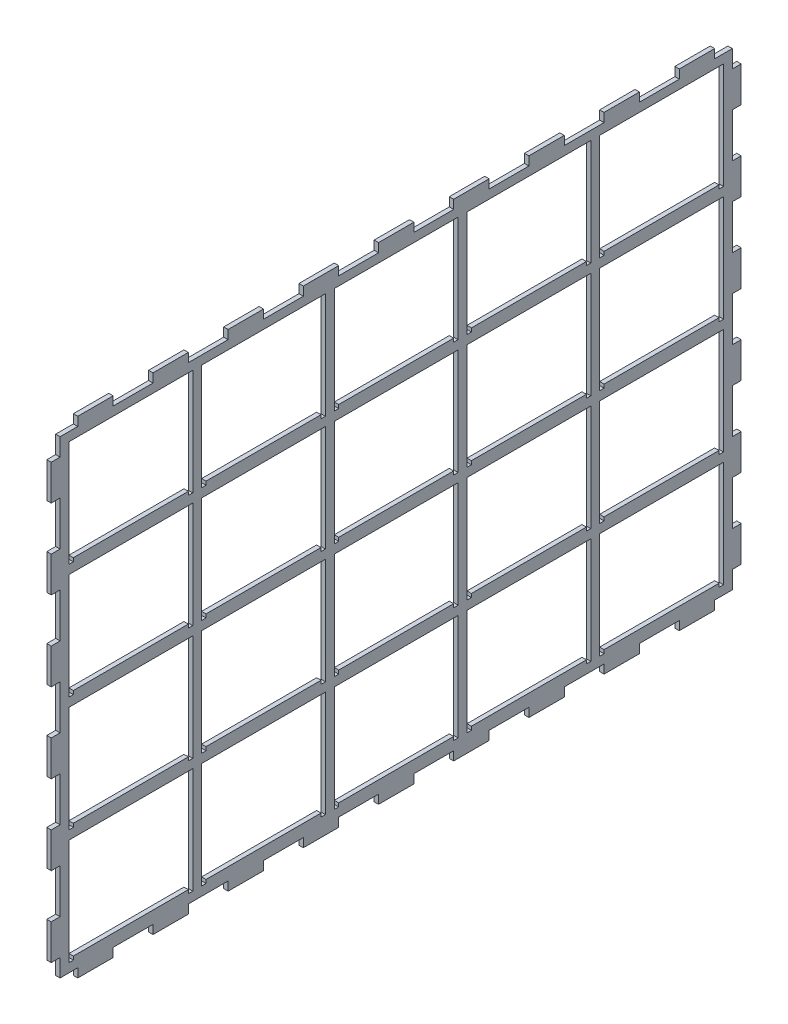
SolidWorks part; units mm, degrees
material "Mahogany"
ref_plane "Front" through (0, 0, 0) normal (0, 0, 1) x (1, 0, 0)
ref_plane "Top" through (0, 0, 0) normal (0, 1, 0) x (1, 0, 0)
ref_plane "Right" through (0, 0, 0) normal (1, 0, 0) x (0, 0, -1)
sketch "Sketch1" plane through (0, 0, 0) normal (1, 0, 0) x (0, 0, -1)
  line L0 (115, 67.5) -> (115, 127.5)
  line L1 (115, 127.5) -> (185, 127.5)
  line L2 (185, 127.5) -> (185, 67.5)
  line L3 (185, 67.5) -> (182.5, 67.5)
  line L4 (182.5, 67.5) -> (182.5, 69.5)
  line L5 (117.5, 69.5) -> (182.5, 69.5)
  line L6 (117.5, 67.5) -> (117.5, 69.5)
  line L7 (117.5, 67.5) -> (115, 67.5)
  line L8 (-190, -132.5) -> (-190, 132.5) construction
  line L9 (-195, -137.5) -> (195, -137.5) construction
  line L10 (-195, -137.5) -> (-195, 137.5) construction
  line L11 (-195, 137.5) -> (195, 137.5) construction
  line L12 (195, -137.5) -> (195, 137.5) construction
  line L13 (-195, -137.5) -> (195, 137.5) construction
  line L14 (-195, 137.5) -> (195, -137.5) construction
  line L15 (-190, 132.5) -> (190, 132.5) construction
  line L16 (190, -132.5) -> (190, 132.5) construction
  line L17 (-190, -132.5) -> (190, -132.5) construction
  line L19 (-180, 137.5) -> (-160, 137.5) construction
  line L20 (-180, 137.5) -> (-180, 132.5)
  line L21 (-180, 132.5) -> (-160, 132.5) construction
  line L22 (-160, 137.5) -> (-160, 132.5)
  line L23 (-180, 137.5) -> (-160, 132.5) construction
  line L24 (-180, 132.5) -> (-160, 137.5) construction
  line L25 (-22.8777, 0) -> (32.9465, 0) construction
  line L27 (0, 22.6378) -> (0, -11.8795) construction
  line L29 (115, 2.5) -> (115, 62.5)
  line L30 (115, 62.5) -> (185, 62.5)
  line L31 (185, 62.5) -> (185, 2.5)
  line L32 (185, 2.5) -> (182.5, 2.5)
  line L33 (182.5, 2.5) -> (182.5, 4.5)
  line L34 (117.5, 4.5) -> (182.5, 4.5)
  line L35 (117.5, 2.5) -> (117.5, 4.5)
  line L36 (117.5, 2.5) -> (115, 2.5)
  line L37 (115, -62.5) -> (115, -2.5)
  line L38 (115, -2.5) -> (185, -2.5)
  line L39 (185, -2.5) -> (185, -62.5)
  line L40 (185, -62.5) -> (182.5, -62.5)
  line L41 (182.5, -62.5) -> (182.5, -60.5)
  line L42 (117.5, -60.5) -> (182.5, -60.5)
  line L43 (117.5, -62.5) -> (117.5, -60.5)
  line L44 (117.5, -62.5) -> (115, -62.5)
  line L45 (115, -127.5) -> (115, -67.5)
  line L46 (115, -67.5) -> (185, -67.5)
  line L47 (185, -67.5) -> (185, -127.5)
  line L48 (185, -127.5) -> (182.5, -127.5)
  line L49 (182.5, -127.5) -> (182.5, -125.5)
  line L50 (117.5, -125.5) -> (182.5, -125.5)
  line L51 (117.5, -127.5) -> (117.5, -125.5)
  line L52 (117.5, -127.5) -> (115, -127.5)
  line L53 (40, 67.5) -> (40, 127.5)
  line L54 (40, 127.5) -> (110, 127.5)
  line L55 (110, 127.5) -> (110, 67.5)
  line L56 (110, 67.5) -> (107.5, 67.5)
  line L57 (107.5, 67.5) -> (107.5, 69.5)
  line L58 (42.5, 69.5) -> (107.5, 69.5)
  line L59 (42.5, 67.5) -> (42.5, 69.5)
  line L60 (42.5, 67.5) -> (40, 67.5)
  line L61 (40, 2.5) -> (40, 62.5)
  line L62 (40, 62.5) -> (110, 62.5)
  line L63 (110, 62.5) -> (110, 2.5)
  line L64 (110, 2.5) -> (107.5, 2.5)
  line L65 (107.5, 2.5) -> (107.5, 4.5)
  line L66 (42.5, 4.5) -> (107.5, 4.5)
  line L67 (42.5, 2.5) -> (42.5, 4.5)
  line L68 (42.5, 2.5) -> (40, 2.5)
  line L69 (40, -62.5) -> (40, -2.5)
  line L70 (40, -2.5) -> (110, -2.5)
  line L71 (110, -2.5) -> (110, -62.5)
  line L72 (110, -62.5) -> (107.5, -62.5)
  line L73 (107.5, -62.5) -> (107.5, -60.5)
  line L74 (42.5, -60.5) -> (107.5, -60.5)
  line L75 (42.5, -62.5) -> (42.5, -60.5)
  line L76 (42.5, -62.5) -> (40, -62.5)
  line L77 (40, -127.5) -> (40, -67.5)
  line L78 (40, -67.5) -> (110, -67.5)
  line L79 (110, -67.5) -> (110, -127.5)
  line L80 (110, -127.5) -> (107.5, -127.5)
  line L81 (107.5, -127.5) -> (107.5, -125.5)
  line L82 (42.5, -125.5) -> (107.5, -125.5)
  line L83 (42.5, -127.5) -> (42.5, -125.5)
  line L84 (42.5, -127.5) -> (40, -127.5)
  line L85 (-35, 67.5) -> (-35, 127.5)
  line L86 (-35, 127.5) -> (35, 127.5)
  line L87 (35, 127.5) -> (35, 67.5)
  line L88 (35, 67.5) -> (32.5, 67.5)
  line L89 (32.5, 67.5) -> (32.5, 69.5)
  line L90 (-32.5, 69.5) -> (32.5, 69.5)
  line L91 (-32.5, 67.5) -> (-32.5, 69.5)
  line L92 (-32.5, 67.5) -> (-35, 67.5)
  line L93 (-35, 2.5) -> (-35, 62.5)
  line L94 (-35, 62.5) -> (35, 62.5)
  line L95 (35, 62.5) -> (35, 2.5)
  line L96 (35, 2.5) -> (32.5, 2.5)
  line L97 (32.5, 2.5) -> (32.5, 4.5)
  line L98 (-32.5, 4.5) -> (32.5, 4.5)
  line L99 (-32.5, 2.5) -> (-32.5, 4.5)
  line L100 (-32.5, 2.5) -> (-35, 2.5)
  line L101 (-35, -62.5) -> (-35, -2.5)
  line L102 (-35, -2.5) -> (35, -2.5)
  line L103 (35, -2.5) -> (35, -62.5)
  line L104 (35, -62.5) -> (32.5, -62.5)
  line L105 (32.5, -62.5) -> (32.5, -60.5)
  line L106 (-32.5, -60.5) -> (32.5, -60.5)
  line L107 (-32.5, -62.5) -> (-32.5, -60.5)
  line L108 (-32.5, -62.5) -> (-35, -62.5)
  line L109 (-35, -127.5) -> (-35, -67.5)
  line L110 (-35, -67.5) -> (35, -67.5)
  line L111 (35, -67.5) -> (35, -127.5)
  line L112 (35, -127.5) -> (32.5, -127.5)
  line L113 (32.5, -127.5) -> (32.5, -125.5)
  line L114 (-32.5, -125.5) -> (32.5, -125.5)
  line L115 (-32.5, -127.5) -> (-32.5, -125.5)
  line L116 (-32.5, -127.5) -> (-35, -127.5)
  line L117 (-110, 67.5) -> (-110, 127.5)
  line L118 (-110, 127.5) -> (-40, 127.5)
  line L119 (-40, 127.5) -> (-40, 67.5)
  line L120 (-40, 67.5) -> (-42.5, 67.5)
  line L121 (-42.5, 67.5) -> (-42.5, 69.5)
  line L122 (-107.5, 69.5) -> (-42.5, 69.5)
  line L123 (-107.5, 67.5) -> (-107.5, 69.5)
  line L124 (-107.5, 67.5) -> (-110, 67.5)
  line L125 (-110, 2.5) -> (-110, 62.5)
  line L126 (-110, 62.5) -> (-40, 62.5)
  line L127 (-40, 62.5) -> (-40, 2.5)
  line L128 (-40, 2.5) -> (-42.5, 2.5)
  line L129 (-42.5, 2.5) -> (-42.5, 4.5)
  line L130 (-107.5, 4.5) -> (-42.5, 4.5)
  line L131 (-107.5, 2.5) -> (-107.5, 4.5)
  line L132 (-107.5, 2.5) -> (-110, 2.5)
  line L133 (-110, -62.5) -> (-110, -2.5)
  line L134 (-110, -2.5) -> (-40, -2.5)
  line L135 (-40, -2.5) -> (-40, -62.5)
  line L136 (-40, -62.5) -> (-42.5, -62.5)
  line L137 (-42.5, -62.5) -> (-42.5, -60.5)
  line L138 (-107.5, -60.5) -> (-42.5, -60.5)
  line L139 (-107.5, -62.5) -> (-107.5, -60.5)
  line L140 (-107.5, -62.5) -> (-110, -62.5)
  line L141 (-110, -127.5) -> (-110, -67.5)
  line L142 (-110, -67.5) -> (-40, -67.5)
  line L143 (-40, -67.5) -> (-40, -127.5)
  line L144 (-40, -127.5) -> (-42.5, -127.5)
  line L145 (-42.5, -127.5) -> (-42.5, -125.5)
  line L146 (-107.5, -125.5) -> (-42.5, -125.5)
  line L147 (-107.5, -127.5) -> (-107.5, -125.5)
  line L148 (-107.5, -127.5) -> (-110, -127.5)
  line L149 (-185, 67.5) -> (-185, 127.5)
  line L150 (-185, 127.5) -> (-115, 127.5)
  line L151 (-115, 127.5) -> (-115, 67.5)
  line L152 (-115, 67.5) -> (-117.5, 67.5)
  line L153 (-117.5, 67.5) -> (-117.5, 69.5)
  line L154 (-182.5, 69.5) -> (-117.5, 69.5)
  line L155 (-182.5, 67.5) -> (-182.5, 69.5)
  line L156 (-182.5, 67.5) -> (-185, 67.5)
  line L157 (-185, 2.5) -> (-185, 62.5)
  line L158 (-185, 62.5) -> (-115, 62.5)
  line L159 (-115, 62.5) -> (-115, 2.5)
  line L160 (-115, 2.5) -> (-117.5, 2.5)
  line L161 (-117.5, 2.5) -> (-117.5, 4.5)
  line L162 (-182.5, 4.5) -> (-117.5, 4.5)
  line L163 (-182.5, 2.5) -> (-182.5, 4.5)
  line L164 (-182.5, 2.5) -> (-185, 2.5)
  line L165 (-185, -62.5) -> (-185, -2.5)
  line L166 (-185, -2.5) -> (-115, -2.5)
  line L167 (-115, -2.5) -> (-115, -62.5)
  line L168 (-115, -62.5) -> (-117.5, -62.5)
  line L169 (-117.5, -62.5) -> (-117.5, -60.5)
  line L170 (-182.5, -60.5) -> (-117.5, -60.5)
  line L171 (-182.5, -62.5) -> (-182.5, -60.5)
  line L172 (-182.5, -62.5) -> (-185, -62.5)
  line L173 (-185, -127.5) -> (-185, -67.5)
  line L174 (-185, -67.5) -> (-115, -67.5)
  line L175 (-115, -67.5) -> (-115, -127.5)
  line L176 (-115, -127.5) -> (-117.5, -127.5)
  line L177 (-117.5, -127.5) -> (-117.5, -125.5)
  line L178 (-182.5, -125.5) -> (-117.5, -125.5)
  line L179 (-182.5, -127.5) -> (-182.5, -125.5)
  line L180 (-182.5, -127.5) -> (-185, -127.5)
  line L182 (-190, 122.5) -> (-195, 122.5)
  line L183 (-190, 122.5) -> (-190, 102.5) construction
  line L184 (-190, 102.5) -> (-195, 102.5)
  line L185 (-195, 122.5) -> (-195, 102.5)
  line L186 (-190, 122.5) -> (-195, 102.5) construction
  line L187 (-190, 102.5) -> (-195, 122.5) construction
  line L188 (190, 102.5) -> (195, 102.5)
  line L189 (195, 122.5) -> (195, 102.5)
  line L190 (190, 122.5) -> (195, 122.5)
  line L191 (-160, 137.5) -> (-180, 137.5)
  line L193 (-160, -137.5) -> (-160, -132.5)
  line L194 (-160, -137.5) -> (-180, -137.5)
  line L195 (-180, -137.5) -> (-180, -132.5)
  line L196 (-117.5, 137.5) -> (-117.5, 132.5)
  line L197 (-117.5, 137.5) -> (-137.5, 137.5)
  line L198 (-137.5, 137.5) -> (-137.5, 132.5)
  line L199 (-117.5, -137.5) -> (-117.5, -132.5)
  line L200 (-117.5, -137.5) -> (-137.5, -137.5)
  line L201 (-137.5, -137.5) -> (-137.5, -132.5)
  line L202 (-75, 137.5) -> (-75, 132.5)
  line L203 (-75, 137.5) -> (-95, 137.5)
  line L204 (-95, 137.5) -> (-95, 132.5)
  line L205 (-75, -137.5) -> (-75, -132.5)
  line L206 (-75, -137.5) -> (-95, -137.5)
  line L207 (-95, -137.5) -> (-95, -132.5)
  line L208 (-32.5, 137.5) -> (-32.5, 132.5)
  line L209 (-32.5, 137.5) -> (-52.5, 137.5)
  line L210 (-52.5, 137.5) -> (-52.5, 132.5)
  line L211 (-32.5, -137.5) -> (-32.5, -132.5)
  line L212 (-32.5, -137.5) -> (-52.5, -137.5)
  line L213 (-52.5, -137.5) -> (-52.5, -132.5)
  line L214 (10, 137.5) -> (10, 132.5)
  line L215 (10, 137.5) -> (-10, 137.5)
  line L216 (-10, 137.5) -> (-10, 132.5)
  line L217 (10, -137.5) -> (10, -132.5)
  line L218 (10, -137.5) -> (-10, -137.5)
  line L219 (-10, -137.5) -> (-10, -132.5)
  line L220 (52.5, 137.5) -> (52.5, 132.5)
  line L221 (52.5, 137.5) -> (32.5, 137.5)
  line L222 (32.5, 137.5) -> (32.5, 132.5)
  line L223 (52.5, -137.5) -> (52.5, -132.5)
  line L224 (52.5, -137.5) -> (32.5, -137.5)
  line L225 (32.5, -137.5) -> (32.5, -132.5)
  line L226 (95, 137.5) -> (95, 132.5)
  line L227 (95, 137.5) -> (75, 137.5)
  line L228 (75, 137.5) -> (75, 132.5)
  line L229 (95, -137.5) -> (95, -132.5)
  line L230 (95, -137.5) -> (75, -137.5)
  line L231 (75, -137.5) -> (75, -132.5)
  line L232 (137.5, 137.5) -> (137.5, 132.5)
  line L233 (137.5, 137.5) -> (117.5, 137.5)
  line L234 (117.5, 137.5) -> (117.5, 132.5)
  line L235 (137.5, -137.5) -> (137.5, -132.5)
  line L236 (137.5, -137.5) -> (117.5, -137.5)
  line L237 (117.5, -137.5) -> (117.5, -132.5)
  line L238 (180, 137.5) -> (180, 132.5)
  line L239 (180, 137.5) -> (160, 137.5)
  line L240 (160, 137.5) -> (160, 132.5)
  line L241 (180, -137.5) -> (180, -132.5)
  line L242 (180, -137.5) -> (160, -137.5)
  line L243 (160, -137.5) -> (160, -132.5)
  line L244 (-190, 77.5) -> (-195, 77.5)
  line L245 (-195, 77.5) -> (-195, 57.5)
  line L246 (-190, 57.5) -> (-195, 57.5)
  line L247 (190, 77.5) -> (195, 77.5)
  line L248 (195, 77.5) -> (195, 57.5)
  line L249 (190, 57.5) -> (195, 57.5)
  line L250 (-190, 32.5) -> (-195, 32.5)
  line L251 (-195, 32.5) -> (-195, 12.5)
  line L252 (-190, 12.5) -> (-195, 12.5)
  line L253 (190, 32.5) -> (195, 32.5)
  line L254 (195, 32.5) -> (195, 12.5)
  line L255 (190, 12.5) -> (195, 12.5)
  line L256 (-190, -12.5) -> (-195, -12.5)
  line L257 (-195, -12.5) -> (-195, -32.5)
  line L258 (-190, -32.5) -> (-195, -32.5)
  line L259 (190, -12.5) -> (195, -12.5)
  line L260 (195, -12.5) -> (195, -32.5)
  line L261 (190, -32.5) -> (195, -32.5)
  line L262 (-190, -57.5) -> (-195, -57.5)
  line L263 (-195, -57.5) -> (-195, -77.5)
  line L264 (-190, -77.5) -> (-195, -77.5)
  line L265 (190, -57.5) -> (195, -57.5)
  line L266 (195, -57.5) -> (195, -77.5)
  line L267 (190, -77.5) -> (195, -77.5)
  line L268 (-190, -102.5) -> (-195, -102.5)
  line L269 (-195, -102.5) -> (-195, -122.5)
  line L270 (-190, -122.5) -> (-195, -122.5)
  line L271 (190, -102.5) -> (195, -102.5)
  line L272 (195, -102.5) -> (195, -122.5)
  line L273 (190, -122.5) -> (195, -122.5)
  line L274 (-180, 132.5) -> (-190, 132.5)
  line L275 (-190, 132.5) -> (-190, 122.5)
  line L277 (-190, -122.5) -> (-190, -132.5)
  line L278 (-190, -132.5) -> (-180, -132.5)
  line L280 (180, -132.5) -> (190, -132.5)
  line L281 (190, -132.5) -> (190, -122.5)
  line L283 (180, 132.5) -> (190, 132.5)
  line L284 (190, 132.5) -> (190, 122.5)
  line L286 (160, 132.5) -> (137.5, 132.5)
  line L288 (160, -132.5) -> (137.5, -132.5)
  line L289 (117.5, -132.5) -> (95, -132.5)
  line L290 (117.5, 132.5) -> (95, 132.5)
  line L291 (75, -132.5) -> (52.5, -132.5)
  line L292 (75, 132.5) -> (52.5, 132.5)
  line L293 (32.5, -132.5) -> (10, -132.5)
  line L294 (32.5, 132.5) -> (10, 132.5)
  line L295 (-10, -132.5) -> (-32.5, -132.5)
  line L296 (-10, 132.5) -> (-32.5, 132.5)
  line L297 (-52.5, -132.5) -> (-75, -132.5)
  line L298 (-52.5, 132.5) -> (-75, 132.5)
  line L299 (-95, -132.5) -> (-117.5, -132.5)
  line L300 (-95, 132.5) -> (-117.5, 132.5)
  line L301 (-137.5, -132.5) -> (-160, -132.5)
  line L302 (-137.5, 132.5) -> (-160, 132.5)
  line L303 (-190, 102.5) -> (-190, 77.5)
  line L305 (190, 102.5) -> (190, 77.5)
  line L306 (190, 57.5) -> (190, 32.5)
  line L307 (-190, 57.5) -> (-190, 32.5)
  line L308 (190, 12.5) -> (190, -12.5)
  line L309 (-190, 12.5) -> (-190, -12.5)
  line L310 (190, -32.5) -> (190, -57.5)
  line L311 (-190, -32.5) -> (-190, -57.5)
  line L312 (190, -77.5) -> (190, -102.5)
  line L313 (-190, -77.5) -> (-190, -102.5)
  point P8 (0, 0)
  point P22 (-170, 135)
  point P27 (183.75, 67.5)
  point P186 (-192.5, 112.5)
  dimension "D1" = 275
  dimension "D2" = 390
  dimension "D3" = 5
  dimension "D4" = 5
  dimension "D5" = 5
  dimension "D6" = 20
  dimension "D7" = 15
  dimension "D8" = 4
  dimension "D9" = 5
  dimension "D10" = 70
  dimension "D11" = 60
  dimension "D12" = 5
  dimension "D13" = 5
  dimension "D14" = 2.5
  dimension "D15" = 2
  dimension "D16" = 15
  dimension "D17" = 9
  dimension "D19" = 15
  dimension "D20" = 15
  dimension "D21" = 8
  dimension "D18" = 6
  dimension "D22" = 5
extrude "Boss-Extrude1" add sketch "Sketch1" along normal blind 2.5
